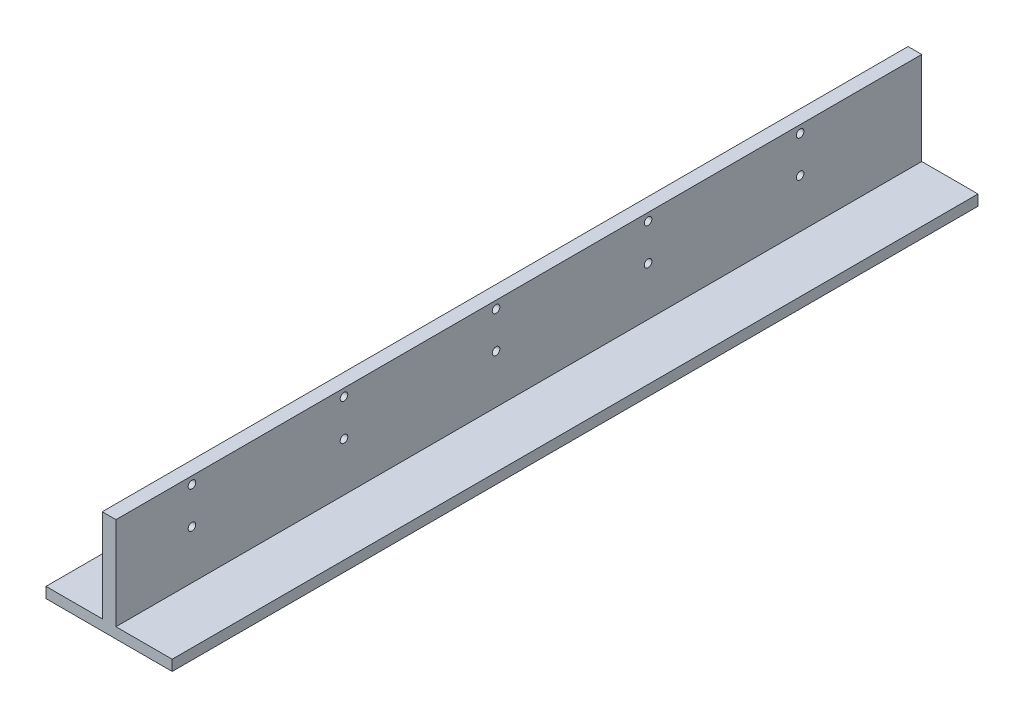
SolidWorks part; units mm, degrees
ref_plane "Plan de face" through (0, 0, 0) normal (0, 0, 1) x (1, 0, 0)
ref_plane "Plan de dessus" through (0, 0, 0) normal (0, 1, 0) x (1, 0, 0)
ref_plane "Plan de droite" through (0, 0, 0) normal (1, 0, 0) x (0, 0, -1)
sketch "Esquisse1" plane through (0, 0, 0) normal (0, 0, 1) x (1, 0, 0)
  line L0 (0, 0) -> (83, 0)
  line L1 (83, 0) -> (83, 7)
  line L2 (83, 7) -> (46, 7)
  line L3 (46, 7) -> (46, 68)
  line L4 (46, 68) -> (37, 68)
  line L5 (37, 68) -> (37, 7)
  line L6 (37, 7) -> (0, 7)
  line L7 (0, 7) -> (0, 0)
  dimension "D1" = 7
  dimension "D2" = 9
  dimension "D3" = 83
  dimension "D4" = 68
extrude "Boss.-Extru.1" add sketch "Esquisse1" along normal blind 530
sketch "Esquisse2" plane through (37, 0, 0) normal (-1, 0, 0) x (0, 0, 1)
  line L0 (0, 51) -> (530, 51) construction
  line L1 (0, 68) -> (0, 7) construction
  line L2 (530, 68) -> (530, 7) construction
  line L3 (530, 68) -> (0, 68) construction
  line L4 (80, 63) -> (180, 63) construction
  circle A0 centre (80, 63) radius 2.5
  circle A1 centre (80, 39) radius 2.5
  circle A2 centre (180, 63) radius 2.5
  circle A3 centre (180, 39) radius 2.5
  circle A4 centre (280, 63) radius 2.5
  circle A5 centre (280, 39) radius 2.5
  circle A6 centre (380, 63) radius 2.5
  circle A7 centre (380, 39) radius 2.5
  circle A8 centre (480, 63) radius 2.5
  circle A9 centre (480, 39) radius 2.5
  dimension "D2" = 12
  dimension "D4" = 5
  dimension "D1" = 17
  dimension "D3" = 80
  dimension "D6" = 100
  dimension "D5" = 5
extrude "Enlèv. mat.-Extru.1" cut sketch "Esquisse2" against normal up to vertex (9 mm away) up to point (46, 68, 0)
